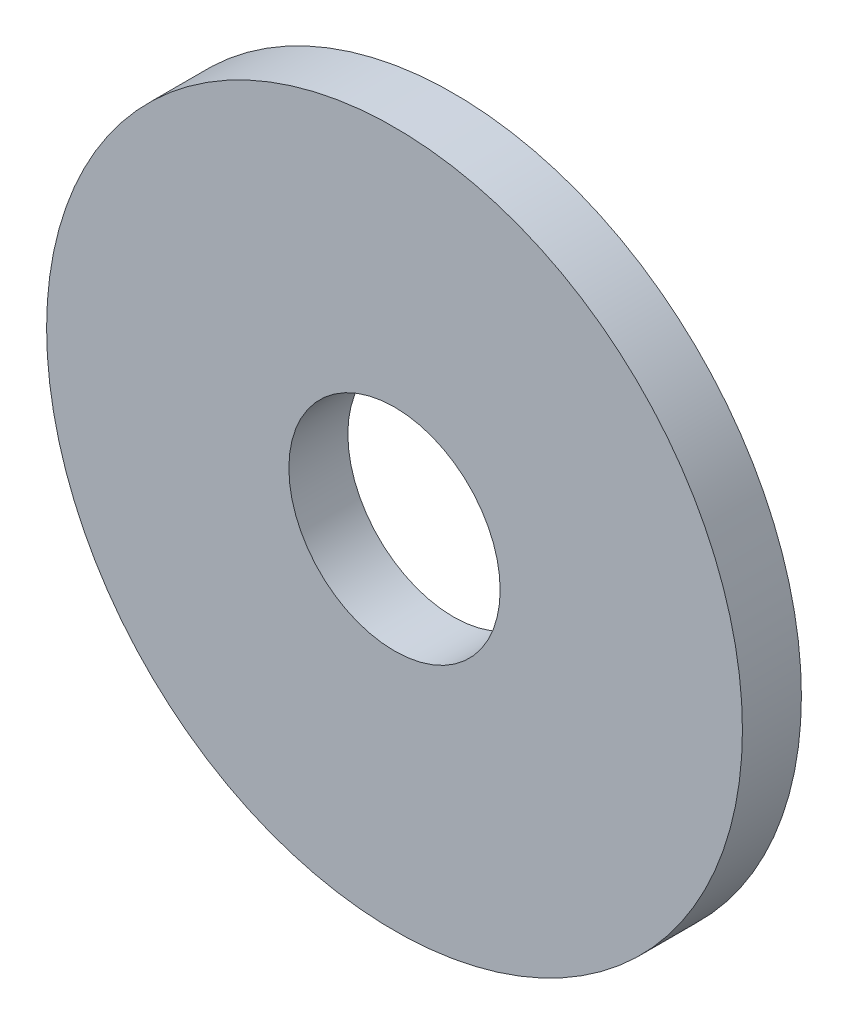
SolidWorks part; units mm, degrees
ref_plane "Front Plane" through (0, 0, 0) normal (0, 0, 1) x (1, 0, 0)
ref_plane "Top Plane" through (0, 0, 0) normal (0, 1, 0) x (1, 0, 0)
ref_plane "Right Plane" through (0, 0, 0) normal (1, 0, 0) x (0, 0, -1)
sketch "Sketch1" plane through (0, 0, 0) normal (0, 0, 1) x (1, 0, 0)
  circle A0 centre (0, 0) radius 7.08
  circle A1 centre (0, 0) radius 2.15
  dimension "D1" = 14.16
  dimension "D2" = 4.3
extrude "Boss-Extrude1" add sketch "Sketch1" along normal mid plane 1.2
